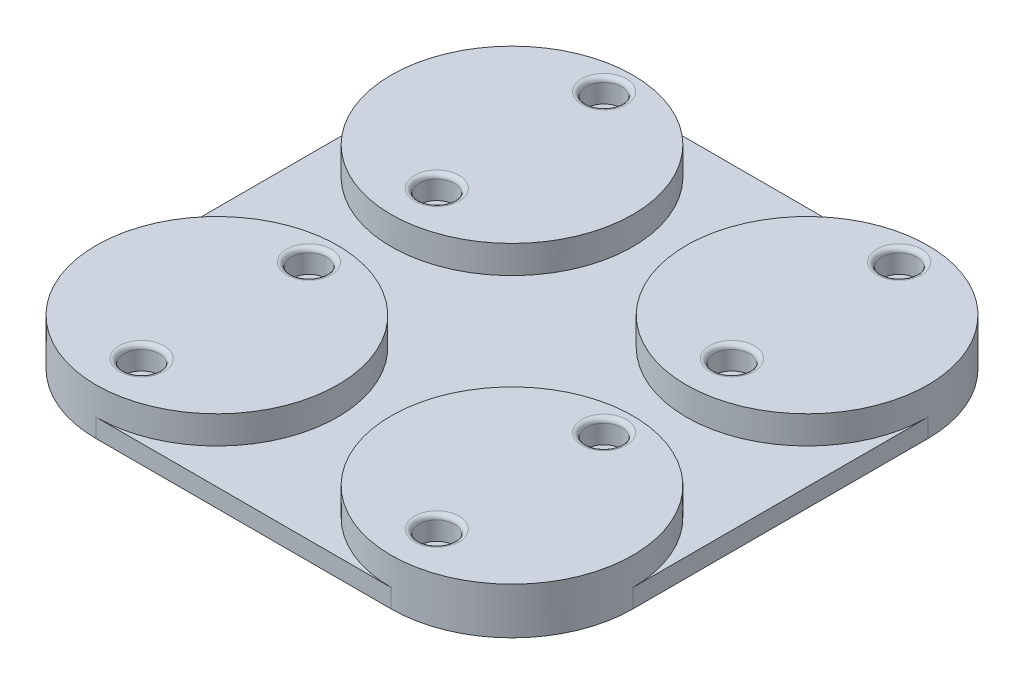
SolidWorks part; units mm, degrees
ref_plane "Front Plane" through (0, 0, 0) normal (0, 0, 1) x (1, 0, 0)
ref_plane "Top Plane" through (0, 0, 0) normal (0, 1, 0) x (1, 0, 0)
ref_plane "Right Plane" through (0, 0, 0) normal (1, 0, 0) x (0, 0, -1)
sketch "Sketch1" plane through (0, 0, 0) normal (0, 1, 0) x (1, 0, 0)
  circle A0 centre (0, 0) radius 13
  dimension "D1" = 26
extrude "Boss-Extrude1" add sketch "Sketch1" along normal blind 3
sketch "Sketch2" plane through (0, 3, 0) normal (0, 1, 0) x (1, 0, 0)
  circle A0 centre (0, 9.906) radius 1.905
  circle A1 centre (0, -8.094) radius 1.905
  dimension "D1" = 3.81
  dimension "D2" = 18
  dimension "D3" = 9.906
extrude "Cut-Extrude1" cut sketch "Sketch2" against normal blind 2.5
pattern_linear "LPattern5" count 2 spacing 31.75 along (0, 0, 1) count 2 spacing 31.75 along (1, 0, 0) of bodies 102
sketch "Sketch3" plane through (0, 0, 0) normal (0, -1, 0) x (1, 0, 0)
  line L0 (-13, 0) -> (-13, 31.75)
  line L1 (0, 44.75) -> (31.75, 44.75)
  line L2 (44.75, 31.75) -> (44.75, 0)
  line L3 (0, -13) -> (31.75, -13)
  circle A3 centre (0, 31.75) radius 13
  arc A4 (0, 44.75) -> (-13, 31.75) centre (0, 31.75) ccw
  circle A5 centre (31.75, 31.75) radius 13
  arc A6 (44.75, 31.75) -> (31.75, 44.75) centre (31.75, 31.75) ccw
  circle A7 centre (31.75, 0) radius 13
  arc A8 (31.75, -13) -> (44.75, 0) centre (31.75, 0) ccw
  circle A9 centre (0, 0) radius 13
  arc A10 (-13, 0) -> (0, -13) centre (0, 0) ccw
  dimension "D1" = 0
  dimension "D2" = 0
  dimension "D3" = 0
  dimension "D4" = 0
extrude "Boss-Extrude2" add sketch "Sketch3" along normal blind 2
sketch "Sketch5" plane through (0, -2, 0) normal (0, -1, 0) x (1, 0, 0)
  line L0 (0, 0) -> (44.75, 0) construction
  line L1 (44.75, 0) -> (44.75, 31.75) construction
  text T0 "Roto-Lock-GB2025"
  point P3 (0, 0)
  point P4 (44.75, 0)
extrude "Cut-Extrude2" cut sketch "Sketch5" against normal blind 0.25
fillet "Fillet1" radius 0.5 8 edges at (0, 3, 41.749) (0, 3, 23.749) (0, 3, 9.999) (0, 3, -8.001) (31.75, 3, -8.001) (31.75, 3, 9.999) (31.75, 3, 23.749) (31.75, 3, 41.749)
